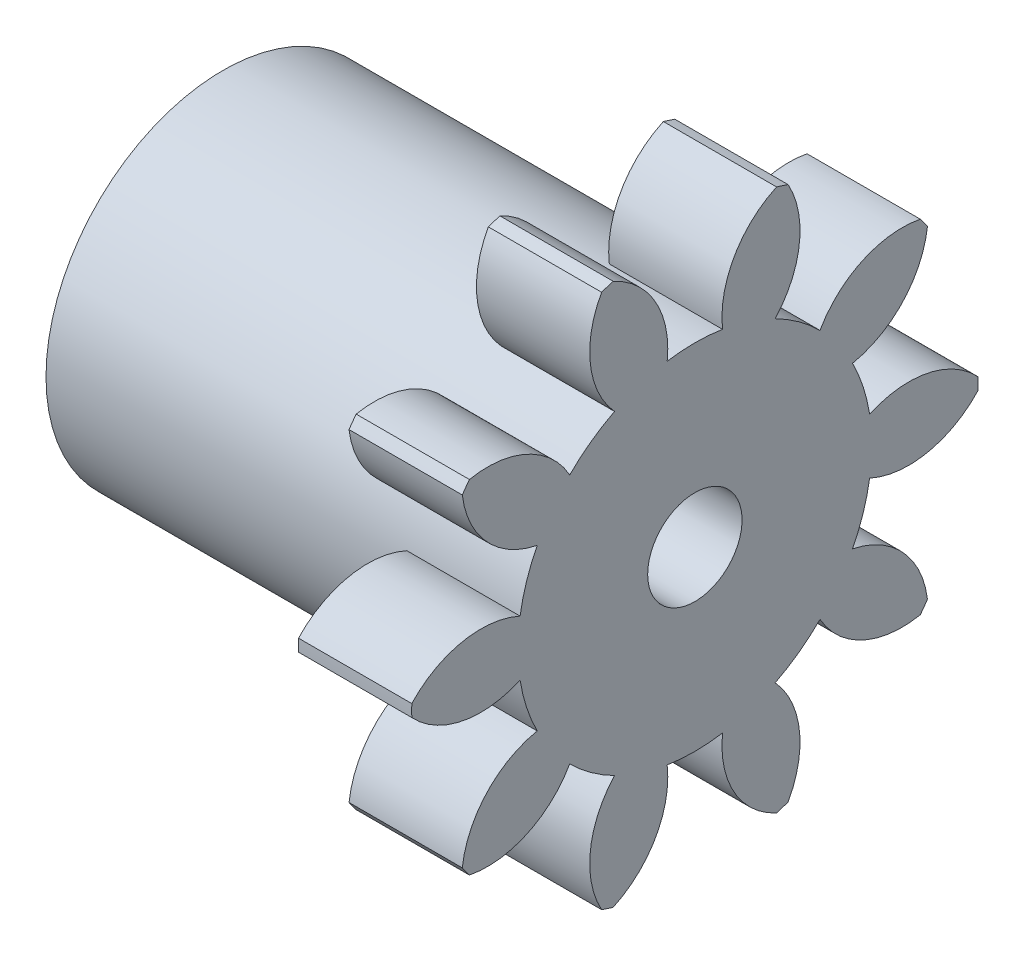
SolidWorks part; units mm, degrees
ref_plane "Plane1" through (0, 0, 0) normal (0, 0, 1) x (1, 0, 0)
ref_plane "Plane2" through (0, 0, 0) normal (0, 1, 0) x (1, 0, 0)
ref_plane "Plane3" through (0, 0, 0) normal (1, 0, 0) x (0, 0, -1)
other "Configuration Table"
sketch "HoldingSke" plane through (0, 0, 0) normal (0, 1, 0) x (1, 0, 0)
  line L0 (0, 0) -> (0.197, -0.0347)
  line L1 (-15, 0) -> (100, 0) construction
  line L2 (0, 0) -> (-2.1039, 2.3779)
  line L3 (0, 0) -> (-11.863, 4.5341)
  line L4 (0, 0) -> (8.5048, 1.4996)
  line L5 (0, 0) -> (-46.8476, -17.4728)
  line L6 (0, 0) -> (-9.9476, -6.7116)
  line L7 (-2.1039, 2.3779) -> (8.6586, 51.2059)
  line L8 (-76.2, 54.61) -> (-74.4, 54.61)
  line L9 (-71.009, 38.7566) -> (-53.1078, 45.2721)
  line L10 (-76.2, 71.12) -> (104.1128, 71.12)
  line L11 (0, 0) -> (-12, 0)
  line L12 (-76.2, 101.6) -> (-76.033, 101.6)
  line L13 (24.9733, 27.94) -> (52.9518, 28.4284)
  line L14 (24.9733, 27.94) -> (24.9743, 27.94)
  line L15 (24.9733, 27.94) -> (100.4006, 29.5858)
  line L16 (-63.627, -5) -> (-12.827, -5)
  circle A0 centre (0, 0) radius 5
  circle A1 centre (0, 0) radius 18.749
  circle A2 centre (0, 0) radius 37.5
  circle A3 centre (0, 0) radius 5
  dimension "MHD" = 37.498
  dimension "Hub_dia" = 75
  dimension "Bore" = 10
  dimension "MBD" = 10
  dimension "Num_teeth" = 10
  dimension "Pitch" = 0.2
  dimension "Overall_len" = 50
  dimension "Show_teeth" = 10
  dimension "Thickness" = 12
  dimension "OAL" = 50.0001
  dimension "T_dim" = 1.8
  dimension "Ap" = 20
  dimension "H" = 19.05
  dimension "Pitch_radius" = 180.3128
  dimension "Width" = 12
  dimension "Backlash" = 0.167
  dimension "Addendum_fac" = 1
  dimension "Dedendum_fac" = 1.25
  dimension "Clearance_fac" = 0.25
  dimension "Dedendum_add" = 0.001
  dimension "Module" = 5
sketch "BasProSke" plane through (0, 0, 0) normal (0, 1, 0) x (1, 0, 0)
  line L0 (-10, 0) -> (60, 0) construction
  line L1 (0, 0) -> (0, 30)
  line L2 (0, 0) -> (12, 0)
  line L3 (12, 0) -> (12, 30)
  line L4 (12, 30) -> (0, 30)
  dimension "Thickness" = 12
  dimension "Diameter" = 60
revolve "Base-Revolve" add sketch "BasProSke" angle 360 about L0
sketch "TooCutSke" plane through (0, 0, 0) normal (1, 0, 0) x (0, 0, -1)
  line L1 (0, 0) -> (0, 107) construction
  line L2 (0, 0) -> (-4.2026, 24.6442) construction
  line L3 (0, 0) -> (-15.2881, 47.0521) construction
  line L4 (-4.2026, 24.6442) -> (-7.6441, 23.526) construction
  arc A0 (2.9333, 18.5181) -> (-2.9333, 18.5181) centre (0, 0) ccw
  arc A1 (8.6913, 28.74) -> (-8.6913, 28.74) centre (0, 0) ccw
  circle A2 centre (0, 0) radius 25 construction
  circle A3 centre (0, 0) radius 23.4923 construction
  arc A4 (-2.9333, 18.5181) -> (-8.6913, 28.74) centre (-12.8686, 19.6542) ccw
  arc A5 (8.6913, 28.74) -> (2.9333, 18.5181) centre (12.8686, 19.6542) ccw
  dimension "Root_dia" = 37.498
  dimension "Overcut_dia" = 60.0508
  dimension "Pitch_dia" = 50
  dimension "Base_dia" = 46.9846
  dimension "Flank_rad" = 10
  dimension "Half_ang" = 18
  dimension "Half_CT" = 3.6186
extrude "ToothCut" cut sketch "TooCutSke" along normal through all
fillet "Breaks" [suppressed] radius 0.1
fillet "RootFillets" [suppressed] radius 1.251
pattern_circular "TeethCuts" count 10 every 36 about axis through (-10, 0, 0) along (1, 0, 0) of "ToothCut", "RootFillets", "Breaks"
sketch "HubNeaOneSke" plane through (0, 0, 0) normal (-1, 0, 0) x (0, 0, 1)
  circle A0 centre (0, 0) radius 18.749
  dimension "Diameter" = 37.498
extrude "HubNearOne" add sketch "HubNeaOneSke" along normal blind 38.0001
sketch "HubNeaBotSke" plane through (0, 0, 0) normal (-1, 0, 0) x (0, 0, 1)
  circle A0 centre (0, 0) radius 18.749
  dimension "Diameter" = 37.498
extrude "HubNearBoth" [suppressed] add sketch "HubNeaBotSke" along normal blind 19
ref_plane "FarPln" through (12, 0, 0) normal (1, 0, 0) x (0, 0, -1)
sketch "HubFarSke" plane through (12, 0, 0) normal (1, 0, 0) x (0, 0, -1)
  circle A0 centre (0, 0) radius 18.749
  dimension "Diameter" = 37.498
extrude "HubFar" [suppressed] add sketch "HubFarSke" along normal blind 19
sketch "BorSke" plane through (0, 0, 0) normal (1, 0, 0) x (0, 0, -1)
  circle A0 centre (0, 0) radius 5
  dimension "Diameter" = 10
extrude "Bore" cut sketch "BorSke" along normal mid plane 100.0001
sketch "KeySke" plane through (0, 0, 0) normal (1, 0, 0) x (0, 0, -1)
  line L0 (-2, 0) -> (-2, 6.8)
  line L1 (-2, 6.8) -> (2, 6.8)
  line L2 (2, 6.8) -> (2, 0)
  line L3 (0, 0) -> (0, 34) construction
  line L4 (-2, 0) -> (2, 0)
  dimension "Offset" = 6.8
  dimension "Width" = 4
extrude "Keyway" [suppressed] cut sketch "KeySke" along normal mid plane 100.0001
pattern_circular "Keyway2" [suppressed] count 2 every 90 about axis through (-10, 0, 0) along (1, 0, 0)
sketch "Sketch1" plane through (12, 0, 0) normal (1, 0, 0) x (0, 0, -1)
  circle A0 centre (0, 0) radius 25
equation "' \"Module@HoldingSke\" = 6.35"
equation "' \"Num_teeth@HoldingSke\" = 12"
equation "' \"Ap@HoldingSke\" =  20"
equation "' \"Ap@HoldingSke\" = 20"
equation "' \"Width@HoldingSke\" = 0.5 * 25.4"
equation "' \"Hub_dia@HoldingSke\"= 1 * 25.4"
equation "' \"Hub_dia@HoldingSke\" = 1 * 25.4"
equation "' \"Overall_len@HoldingSke\" = 1.0 * 25.4"
equation "' \"Bore@HoldingSke\" = 0.75 * 25.4"
equation "' \"T_dim@HoldingSke\" = 0.1 * 25.4"
equation "' \"Width@KeySke\" = 0.25 * 25.4"
equation "' \"Show_teeth@HoldingSke\" = 13"
equation "' \"Backlash@HoldingSke\" = 0.009 * 25.4"
equation "' \"Addendum_fac@HoldingSke\" = 1.0"
equation "' \"Dedendum_fac@HoldingSke\" = 1.25"
equation "' \"Dedendum_add@HoldingSke\" = 0.00005 * 25.4"
equation "' \"Clearance_fac@HoldingSke\" = 0.25"
equation "\"Pitch@HoldingSke\" = 1 / \"Module@HoldingSke\""
equation "\"Overcut_dia@TooCutSke\" = (\"Num_teeth@HoldingSke\" + 2 * \"Addendum_fac@HoldingSke\") / \"Pitch@HoldingSke\" + 0.002 * 25.4"
equation "\"Pitch_dia@TooCutSke\" = \"Num_teeth@HoldingSke\" / \"Pitch@HoldingSke\""
equation "\"Base_dia@TooCutSke\" = \"Num_teeth@HoldingSke\" / \"Pitch@HoldingSke\" * cos((\"Ap@HoldingSke\"  * 3.14159265 / 180))"
equation "\"Root_dia@TooCutSke\" = (\"Num_teeth@HoldingSke\" + 2) / \"Pitch@HoldingSke\" - 2 * (\"Addendum_fac@HoldingSke\" + \"Dedendum_fac@HoldingSke\") / \"Pitch@HoldingSke\" - \"Dedendum_add@HoldingSke\" * 2"
equation "\"Half_ang@TooCutSke\" = 180 / \"Num_teeth@HoldingSke\""
equation "\"Half_CT@TooCutSke\" = \"Num_teeth@HoldingSke\" / \"Pitch@HoldingSke\" * sin((3.14159265 / 2 / \"Num_teeth@HoldingSke\")) / 2 - 7 * \"Backlash@HoldingSke\" / 4"
equation "\"Flank_rad@TooCutSke\" = \"Num_teeth@HoldingSke\" / \"Pitch@HoldingSke\" / 5"
equation "\"Radius@RootFillets\" = \"Clearance_fac@HoldingSke\" / \"Pitch@HoldingSke\" + \"Dedendum_add@HoldingSke\""
equation "\"Break_rad@Breaks\" = 0.02 / \"Pitch@HoldingSke\""
equation "\"Thickness@HoldingSke\" = \"Width@HoldingSke\""
equation "\"OAL@HoldingSke\" = \"Thickness@HoldingSke\""
equation "\"MHD@HoldingSke\" = (\"Num_teeth@HoldingSke\" + 2) / \"Pitch@HoldingSke\" - 2 * (\"Addendum_fac@HoldingSke\" + \"Dedendum_fac@HoldingSke\")  / \"Pitch@HoldingSke\" - \"Dedendum_add@HoldingSke\" * 2"
equation "\"MBD@HoldingSke\" = (\"Num_teeth@HoldingSke\" + 2) / \"Pitch@HoldingSke\" - 2 * (\"Addendum_fac@HoldingSke\" + \"Dedendum_fac@HoldingSke\")  / \"Pitch@HoldingSke\" - \"Dedendum_add@HoldingSke\" * 2 - 0.002 * 25.4"
equation "\"MHD@HoldingSke\" = ((sgn( \"MHD@HoldingSke\" - \"Hub_dia@HoldingSke\" )-1)*( \"MHD@HoldingSke\" - \"Hub_dia@HoldingSke\" ))/-2+ \"Hub_dia@HoldingSke\""
equation "\"MBD@HoldingSke\" = ((sgn( \"MBD@HoldingSke\" - \"Bore@HoldingSke\" )-1)*( \"MBD@HoldingSke\" - \"Bore@HoldingSke\" ))/-2+ \"Bore@HoldingSke\""
equation "\"OAL@HoldingSke\" = ((sgn( \"OAL@HoldingSke\" - \"Overall_len@HoldingSke\" )+1)*( \"OAL@HoldingSke\" - \"Overall_len@HoldingSke\" ))/2 + \"Overall_len@HoldingSke\" + 0.000002 * 25.4"
equation "\"Num_teeth@TeethCuts\" = int( \"Show_teeth@HoldingSke\" ) + 1"
equation "\"Num_teeth@TeethCuts\" = ((sgn( \"Num_teeth@TeethCuts\" - \"Num_teeth@HoldingSke\" )-1)*( \"Num_teeth@TeethCuts\" - \"Num_teeth@HoldingSke\" ))/-2+ \"Num_teeth@HoldingSke\""
equation "\"Num_teeth@TeethCuts\" = ((sgn( \"Num_teeth@TeethCuts\" - 2.0)+1)*( \"Num_teeth@TeethCuts\" - 2.0))/2 +2.0"
equation "\"Angle@TeethCuts\" = 360.0 / \"Num_teeth@HoldingSke\""
equation "\"Diameter@BasProSke\" = (\"Num_teeth@HoldingSke\" + 2 * \"Addendum_fac@HoldingSke\") / \"Pitch@HoldingSke\""
equation "\"Thickness@BasProSke\"  = \"Thickness@HoldingSke\""
equation "' \"Fillet_rad@BasProSke\" =  \"Thickness@HoldingSke\" * 0.05"
equation "' \"Fillet_rad@BasProSke\" = \"Thickness@HoldingSke\" * 0.05"
equation "\"MHD@HoldingSke\" = ((sgn( \"MHD@HoldingSke\" - \"Root_dia@TooCutSke\" )-1)*( \"MHD@HoldingSke\" - \"Root_dia@TooCutSke\" ))/-2+ \"Root_dia@TooCutSke\""
equation "\"Diameter@HubNeaOneSke\" = \"MHD@HoldingSke\""
equation "\"Length@HubNearOne\" = \"OAL@HoldingSke\" - \"Thickness@BasProSke\""
equation "\"Diameter@HubNeaBotSke\" = \"MHD@HoldingSke\""
equation "\"Length@HubNearBoth\" = ( \"OAL@HoldingSke\" - \"Thickness@BasProSke\" ) / 2.0"
equation "\"Thickness@FarPln\" = \"Thickness@BasProSke\""
equation "\"Diameter@HubFarSke\" = \"MHD@HoldingSke\""
equation "\"Length@HubFar\" = ( \"OAL@HoldingSke\" - \"Thickness@BasProSke\" ) / 2.0"
equation "\"Diameter@BorSke\" = \"MBD@HoldingSke\""
equation "\"D1@Bore\" = \"OAL@HoldingSke\" * 2.0"
equation "\"D1@Keyway\" = \"OAL@HoldingSke\" * 2.0"
equation "\"Offset@KeySke\" = \"T_dim@HoldingSke\" + \"MBD@HoldingSke\" / 2.0"
